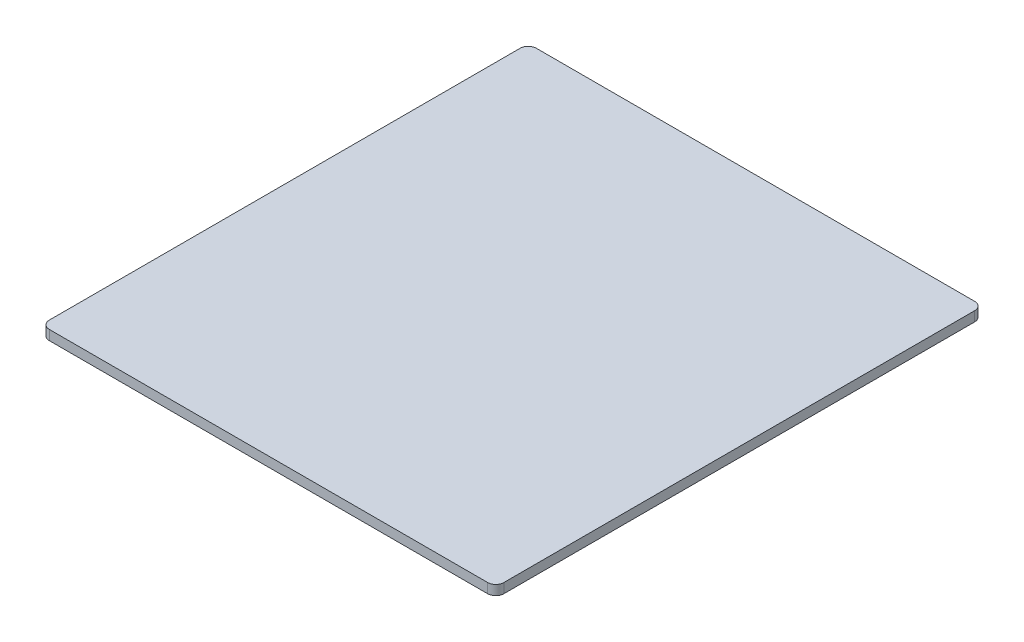
SolidWorks part; units mm, degrees
ref_plane "Front Plane" through (0, 0, 0) normal (0, 0, 1) x (1, 0, 0)
ref_plane "Top Plane" through (0, 0, 0) normal (0, 1, 0) x (1, 0, 0)
ref_plane "Right Plane" through (0, 0, 0) normal (1, 0, 0) x (0, 0, -1)
sketch "Sketch1" plane through (0, 0, 0) normal (0, 1, 0) x (1, 0, 0)
  line L1 (-140, -150) -> (140, -150)
  line L2 (-140, -150) -> (-140, 150)
  line L3 (-140, 150) -> (140, 150)
  line L4 (140, -150) -> (140, 150)
  line L5 (-140, -150) -> (140, 150) construction
  line L6 (-140, 150) -> (140, -150) construction
  point P0 (0, 0)
  dimension "D1" = 300
  dimension "D2" = 280
extrude "Boss-Extrude1" add sketch "Sketch1" along normal blind 6
fillet "Fillet1" radius 5 4 edges at (-140, 3, -150) (140, 3, -150) (-140, 3, 150) (140, 3, 150)
sketch "Sketch2" plane through (0, 0, 0) normal (0, -1, 0) x (-1, 0, 0)
  circle A0 centre (0, 136.8834) radius 3
  circle A1 centre (-35, 136.8834) radius 3
  circle A2 centre (35.0735, 136.8834) radius 3
  dimension "D1" = 6
  dimension "D2" = 6
  dimension "D3" = 6
extrude "Cut-Extrude1" cut sketch "Sketch2" against normal blind 5
cosmetic thread "Cosmetic Thread1" parameters "D2"=10
cosmetic thread "Cosmetic Thread2" parameters "D2"=10
cosmetic thread "Cosmetic Thread3" parameters "D2"=10
sketch "Sketch3" plane through (0, 0, 0) normal (0, -1, 0) x (-1, 0, 0)
  circle A0 centre (103.5, 73) radius 3
  circle A1 centre (103.5, 87) radius 3
  circle A2 centre (-105.5, 73) radius 3
  circle A3 centre (-105.5, 87) radius 3
  dimension "D1" = 6
  dimension "D2" = 6
  dimension "D3" = 6
  dimension "D4" = 6
extrude "Cut-Extrude2" cut sketch "Sketch3" against normal blind 5
